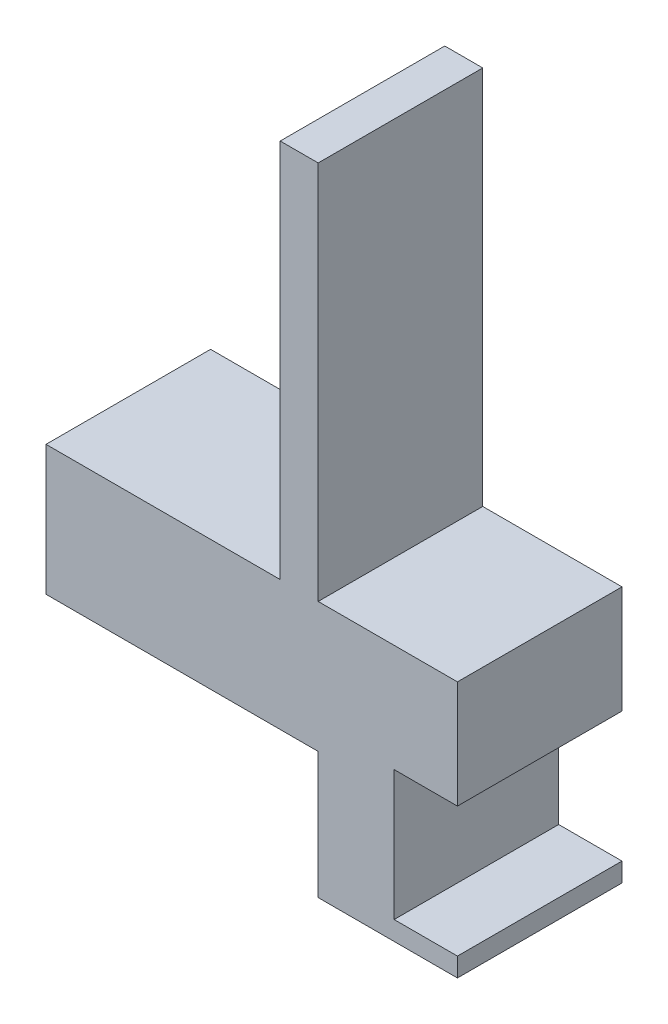
SolidWorks part; units mm, degrees
ref_plane "Front Plane" through (0, 0, 0) normal (0, 0, 1) x (1, 0, 0)
ref_plane "Top Plane" through (0, 0, 0) normal (0, 1, 0) x (1, 0, 0)
ref_plane "Right Plane" through (0, 0, 0) normal (1, 0, 0) x (0, 0, -1)
sketch "Sketch1" plane through (0, 0, 0) normal (0, 0, 1) x (1, 0, 0)
  line L0 (45, 20.52) -> (65, 20.52)
  line L1 (0, 0) -> (43, 0)
  line L2 (0, 0) -> (0, 20.52)
  line L3 (0, 20.52) -> (45, 20.52)
  line L5 (65, 20.52) -> (65, 3.52)
  line L6 (65, -20) -> (43, -20)
  line L7 (43, -20) -> (43, 0)
  line L8 (65, 3.52) -> (55, 3.52)
  line L9 (55, 3.52) -> (55, -17)
  line L10 (55, -17) -> (65, -17)
  line L11 (65, -17) -> (65, -20)
  dimension "D1" = 20
  dimension "D2" = 20.52
  dimension "D3" = 45
  dimension "D4" = 10
  dimension "D5" = 20.52
  dimension "D6" = 20
  dimension "D7" = 3
extrude "Boss-Extrude1" add sketch "Sketch1" along normal blind 26
sketch "Sketch2" plane through (0, 20.52, 0) normal (0, 1, 0) x (1, 0, 0)
  line L0 (0, -26) -> (0, 0) construction
  line L1 (37, 0) -> (43, 0)
  line L2 (37, 0) -> (37, -26)
  line L3 (37, -26) -> (43, -26)
  line L4 (43, 0) -> (43, -26)
  line L5 (65, 0) -> (0, 0) construction
  line L6 (65, -26) -> (0, -26) construction
  dimension "D1" = 37
  dimension "D2" = 6
extrude "Boss-Extrude2" add sketch "Sketch2" along normal blind 60
sketch "Sketch3" plane through (37, 0, 0) normal (-1, 0, 0) x (0, 0, 1)
  line L0 (5.1, 70.52) -> (20.9, 70.52) construction
  line L1 (5.1, 75.77) -> (20.9, 75.77)
  line L2 (5.1, 75.77) -> (5.1, 65.27)
  line L3 (5.1, 65.27) -> (20.9, 65.27)
  line L4 (20.9, 75.77) -> (20.9, 65.27)
  line L5 (0, 20.52) -> (26, 20.52) construction
  line L6 (13, 80.52) -> (13, 20.52) construction
  line L7 (0, 80.52) -> (26, 80.52) construction
  line L8 (13, 75.77) -> (13, 65.27) construction
  dimension "D1" = 50
  dimension "D2" = 10.5
  dimension "D3" = 15.8
extrude "Cut-Extrude1" cut sketch "Sketch3" against normal blind 3
